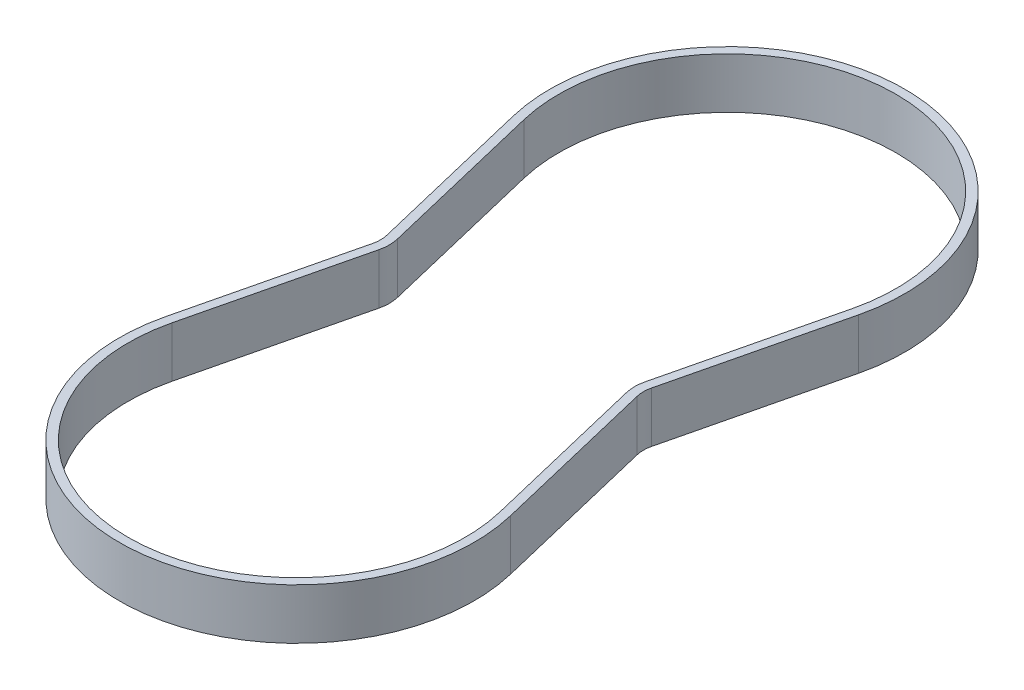
SolidWorks part; units mm, degrees
material "聚亚安酯(11671)"
ref_plane "前视基准面" through (0, 0, 0) normal (0, 0, 1) x (1, 0, 0)
ref_plane "上视基准面" through (0, 0, 0) normal (0, 1, 0) x (1, 0, 0)
ref_plane "右视基准面" through (0, 0, 0) normal (1, 0, 0) x (0, 0, -1)
sketch "草图1" plane through (0, 0, 0) normal (0, 1, 0) x (1, 0, 0)
  line L0 (0, -42.5) -> (0, 42.5) construction
  line L1 (-31.945, 0) -> (31.945, 0) construction
  line L2 (-34.029, 34.3131) -> (-26.1115, 1.4035)
  line L3 (-26.1115, -1.4035) -> (-34.029, -34.3131)
  line L4 (34.029, 34.3131) -> (26.1115, 1.4035)
  line L5 (34.029, -34.3131) -> (26.1115, -1.4035)
  line L6 (-32.3373, 34.7201) -> (-24.4197, 1.8105)
  line L7 (-24.4197, -1.8105) -> (-32.3373, -34.7201)
  line L8 (24.4197, 1.8105) -> (32.3373, 34.7201)
  line L9 (32.3373, -34.7201) -> (24.4197, -1.8105)
  arc A0 (32.3373, 34.7201) -> (-32.3373, 34.7201) centre (0, 42.5) ccw
  arc A1 (-32.3373, -34.7201) -> (32.3373, -34.7201) centre (0, -42.5) ccw
  arc A2 (-26.1115, -1.4035) -> (-26.1115, 1.4035) centre (-31.945, 0) ccw
  arc A3 (34.029, 34.3131) -> (-34.029, 34.3131) centre (0, 42.5) ccw
  arc A4 (-34.029, -34.3131) -> (34.029, -34.3131) centre (0, -42.5) ccw
  circle A5 centre (0, 42.5) radius 35 construction
  circle A6 centre (0, -42.5) radius 35 construction
  arc A7 (26.1115, 1.4035) -> (26.1115, -1.4035) centre (31.945, 0) ccw
  arc A8 (-24.4197, -1.8105) -> (-24.4197, 1.8105) centre (-31.945, 0) ccw
  circle A9 centre (0, 42.5) radius 33.26 construction
  circle A10 centre (0, -42.5) radius 33.26 construction
  arc A11 (24.4197, 1.8105) -> (24.4197, -1.8105) centre (31.945, 0) ccw
  dimension "D1" = 66.52
  dimension "D2" = 85
  dimension "D4" = 12
  dimension "D3" = 63.89
  dimension "D5" = 1.74
  dimension "D6" = 1.74
extrude "凸台-拉伸1" add sketch "草图1" along normal blind 10
